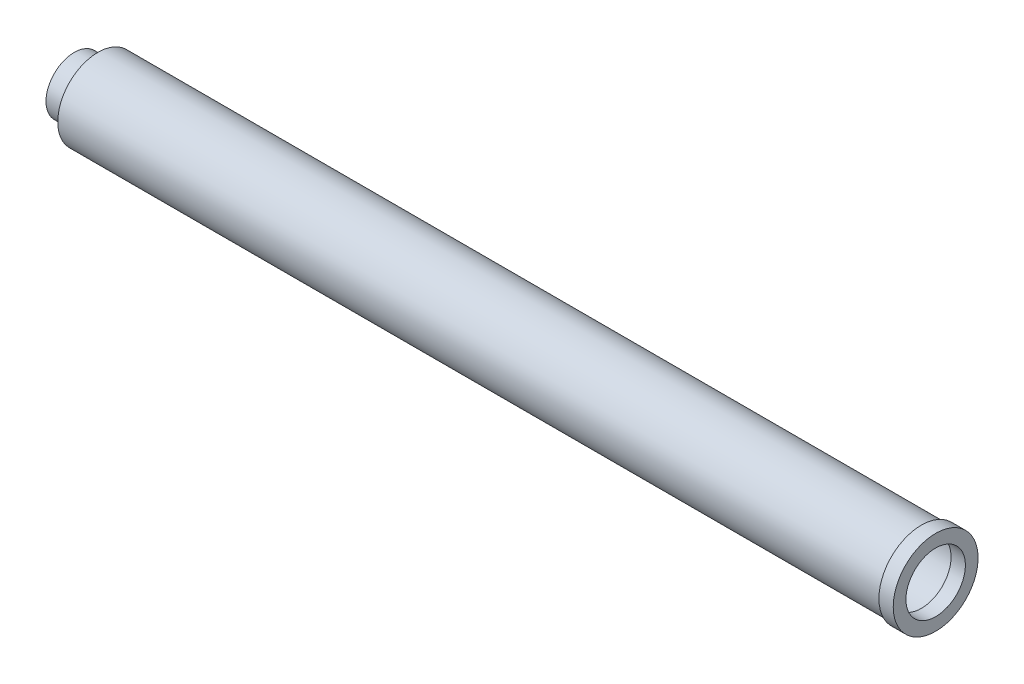
SolidWorks part; units mm, degrees
ref_plane "Ebene vorne" through (0, 0, 0) normal (0, 0, 1) x (1, 0, 0)
ref_plane "Ebene oben" through (0, 0, 0) normal (0, 1, 0) x (1, 0, 0)
ref_plane "Ebene rechts" through (0, 0, 0) normal (1, 0, 0) x (0, 0, -1)
sketch "Sketch1" plane through (0, 0, 0) normal (0, 0, 1) x (1, 0, 0)
  line L0 (-404.7901, 0) -> (397.65, 0) construction
  line L2 (357.2493, 27) -> (-192.7507, 27)
  line L3 (357.2493, 27) -> (357.2493, 25.4)
  line L4 (357.2493, 25.4) -> (-192.7507, 25.4)
  line L5 (-192.7507, 27) -> (-192.7507, 25.4)
  dimension "D1" = 550
  dimension "D2" = 1.6
  dimension "D3" = 54
revolve "Revolve1" add sketch "Sketch1" angle 360 about L0
sketch "Sketch2" plane through (0, 0, 0) normal (0, 0, 1) x (1, 0, 0)
  line L0 (-209.8825, 0) -> (367.4255, 0) construction
  line L1 (357.2493, -27) -> (357.2493, 27) construction
  line L2 (366.8493, 28.5) -> (357.2493, 28.5)
  line L3 (366.8493, 28.5) -> (366.8493, 19.9751)
  line L4 (366.8493, 19.9751) -> (357.2493, 19.9751)
  line L5 (357.2493, 28.5) -> (357.2493, 19.9751)
  line L6 (-176.7507, 27) -> (-176.7507, 14.5)
  line L7 (357.2493, 27) -> (-192.7507, 27) construction
  line L8 (-176.7507, 14.5) -> (-202.2607, 14.5)
  line L9 (-202.2607, 14.5) -> (-202.2607, 0)
  line L10 (-176.7507, 27) -> (-195.8507, 27)
  line L11 (-195.8507, 27) -> (-195.8507, 19)
  line L12 (-195.8507, 19) -> (-211.7507, 19)
  line L13 (-211.7507, 19) -> (-211.7507, 11)
  line L14 (-211.7507, 11) -> (-204.2507, 11)
  line L15 (-204.2507, 11) -> (-204.2507, 0)
  line L16 (-204.2507, 0) -> (-202.2607, 0)
  line L17 (-192.7507, 27) -> (-192.7507, -27) construction
  dimension "D1" = 57
  dimension "D2" = 9.6
  dimension "D3" = 3.1
  dimension "D4" = 16
  dimension "D5" = 29
  dimension "D6" = 38
  dimension "D7" = 22
  dimension "D8" = 7.5
  dimension "D9" = 25.51
  dimension "D10" = 35
revolve "Revolve2" add sketch "Sketch2" angle 360 about L0
